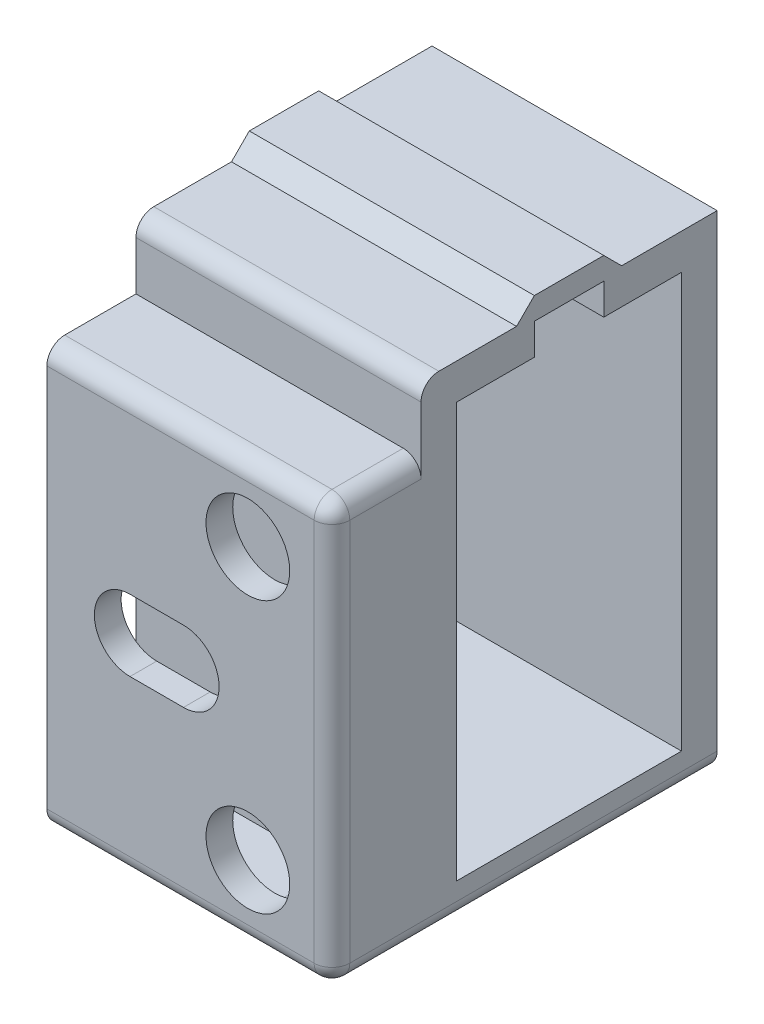
SolidWorks part; units mm, degrees
ref_plane "Front Plane" through (0, 0, 0) normal (0, 0, 1) x (1, 0, 0)
ref_plane "Top Plane" through (0, 0, 0) normal (0, 1, 0) x (1, 0, 0)
ref_plane "Right Plane" through (0, 0, 0) normal (1, 0, 0) x (0, 0, -1)
sketch "Sketch1" plane through (0, 0, 0) normal (1, 0, 0) x (0, 0, -1)
  line L16 (6.3079, 6.3079) -> (-6.3079, 6.3079)
  line L17 (-6.3079, 6.3079) -> (-6.3079, -16.9632)
  line L18 (-6.3079, -16.9632) -> (6.3079, -16.9632)
  line L22 (6.3079, -16.9632) -> (6.3079, 6.3079)
  line L23 (6.0579, 6.0579) -> (-6.0579, 6.0579)
  line L24 (6.0579, -16.7132) -> (6.0579, 6.0579)
  line L25 (-6.0579, -16.7132) -> (6.0579, -16.7132)
  line L26 (-6.0579, 6.0579) -> (-6.0579, -16.7132)
  line L27 (6.0579, 6.0579) -> (-6.0579, 6.0579) construction
  line L28 (6.0579, -16.7132) -> (6.0579, 6.0579) construction
  line L29 (-6.0579, -16.7132) -> (6.0579, -16.7132) construction
  line L30 (-6.0579, 6.0579) -> (-6.0579, -16.7132) construction
  line L31 (8.3079, 8.3079) -> (-8.3079, 8.3079)
  line L32 (-8.3079, 8.3079) -> (-8.3079, -18.9632)
  line L33 (-8.3079, -18.9632) -> (8.3079, -18.9632)
  line L34 (8.3079, -18.9632) -> (8.3079, 8.3079)
  dimension "D1" = 0
  dimension "D2" = 0.25
  dimension "D3" = 2
extrude "Boss-Extrude1" add sketch "Sketch1" along normal mid plane 16
sketch "Sketch2" plane through (-8, 0, 0) normal (-1, 0, 0) x (0, 0, 1)
  line L0 (-1.9478, 5.5579) -> (1.9478, 5.5579)
  line L1 (1.9478, 5.5579) -> (1.9478, 8.0579)
  line L3 (-1.9478, 8.0579) -> (-1.9478, 5.5579)
  line L4 (-1.4478, 6.0579) -> (1.4478, 6.0579)
  line L5 (1.4478, 6.0579) -> (1.4478, 12.1539)
  line L6 (1.4478, 12.1539) -> (-1.4478, 12.1539)
  line L7 (-1.4478, 12.1539) -> (-1.4478, 6.0579)
  line L8 (-1.4478, 6.0579) -> (1.4478, 6.0579) construction
  line L9 (1.4478, 6.0579) -> (1.4478, 12.1539) construction
  line L10 (1.4478, 12.1539) -> (-1.4478, 12.1539) construction
  line L11 (-1.4478, 12.1539) -> (-1.4478, 6.0579) construction
  line L12 (-1.9478, 8.0579) -> (1.9478, 8.0579)
  line L13 (-1.9478, 12.6539) -> (-1.9478, 5.5579) construction
  line L14 (1.9478, 12.6539) -> (-1.9478, 12.6539) construction
  line L15 (1.9478, 5.5579) -> (1.9478, 12.6539) construction
  dimension "D3" = 2
  dimension "D1" = 0
  dimension "D2" = 0.5
extrude "Cut-Extrude2" cut sketch "Sketch2" against normal through all
sketch "Sketch3" plane through (0, 0, 0) normal (0, 0, 1) x (1, 0, 0)
  line B0 (-15.4169, 7.595) -> (-15.4169, -7.595) construction
  line B1 (-12.7469, -10.265) -> (-0.3069, -10.265) construction
  line B2 (2.3631, -7.595) -> (2.3631, 7.595) construction
  line B3 (-0.3069, 10.265) -> (-12.7469, 10.265) construction
  circle B4 centre (-0.1369, -7.615) radius 1.2 construction
  circle B5 centre (-0.1369, 7.615) radius 1.2 construction
  arc B6 (-12.7469, 10.265) -> (-15.4169, 7.595) centre (-12.7469, 7.595) ccw construction
  arc B7 (-15.4169, -7.595) -> (-12.7469, -10.265) centre (-12.7469, -7.595) ccw construction
  arc B8 (-0.3069, -10.265) -> (2.3631, -7.595) centre (-0.3069, -7.595) ccw construction
  arc B9 (2.3631, 7.595) -> (-0.3069, 10.265) centre (-0.3069, 7.595) ccw construction
sketch_block_instance "Block1-1"
sketch_block "Block1"
sketch "Sketch5" plane through (0, 0, 8.3079) normal (0, 0, 1) x (1, 0, 0)
  line L0 (5.78, -7.1982) -> (0.4676, -7.1982) construction
  line L1 (-8, 8.3079) -> (-8, -18.9632) construction
  line L2 (8, 8.3079) -> (8, -18.9632) construction
  line L3 (8, -18.9632) -> (-8, -18.9632)
  line L4 (8, -18.9632) -> (8, 4.5668)
  line L5 (8, 4.5668) -> (-8, 4.5668)
  line L6 (-8, -18.9632) -> (-8, 4.5668)
  line L7 (3.11, 3.0668) -> (3.11, 4.5668) construction
  line L8 (3.11, -17.4632) -> (3.11, -18.9632) construction
  point P2 (-8, -22.0591)
  line B0 (-12, 0.3968) -> (-12, -14.7932) construction
  line B1 (-9.33, -17.4632) -> (3.11, -17.4632) construction
  line B2 (5.78, -14.7932) -> (5.78, 0.3968) construction
  line B3 (3.11, 3.0668) -> (-9.33, 3.0668) construction
  circle B4 centre (3.28, -14.8132) radius 1.2 construction
  circle B5 centre (3.28, 0.4168) radius 1.2 construction
  arc B6 (-9.33, 3.0668) -> (-12, 0.3968) centre (-9.33, 0.3968) ccw construction
  arc B7 (-12, -14.7932) -> (-9.33, -17.4632) centre (-9.33, -14.7932) ccw construction
  arc B8 (3.11, -17.4632) -> (5.78, -14.7932) centre (3.11, -14.7932) ccw construction
  arc B9 (5.78, 0.3968) -> (3.11, 3.0668) centre (3.11, 0.3968) ccw construction
  line M10 (-8, 8.3079) -> (-8, -18.9632)
  line M12 (8, -18.9632) -> (8, 8.3079)
  line M13 (8, 8.3079) -> (-8, 8.3079)
  dimension "D1" = 4
  dimension "D2" = 1.5
sketch_block_instance "Block1-4"
extrude "Boss-Extrude2" add sketch "Sketch5" along normal blind 0.0001 contours L3 M12 M13 M10 | L6 L4 L5 M13
hole_wizard "M2 Clearance Hole1" positions "Sketch6" profile "Sketch7" hole size "M2" standard "ANSI Metric"
sketch "Sketch6" plane through (0, 0, 8.308) normal (0, 0, 1) x (1, 0, 0)
  point P0 (3.28, 0.4168)
  point P2 (3.28, -14.8132)
sketch "Sketch7" plane through (3.28, 0.4168, 8.308) normal (1, 0, 0) x (0, -1, 0)
  line L0 (0, 0) -> (0, 2.7201)
  line L1 (0, 2.7201) -> (1.2, 1.9991)
  line L2 (1.2, 1.9991) -> (1.2, 0)
  line L5 (1.2, 0) -> (0, 0)
  line L10 (0, 2.7201) -> (-1.2, 1.9991) construction
  line L11 (0, -6.35) -> (0, 107.95) construction
  dimension "Hole Dia." = 2.4
  dimension "Hole Depth" = 1.9991
  dimension "Drill Angle" = 118
sketch "Sketch8" plane through (0, 0, 8.308) normal (0, 0, 1) x (1, 0, 0)
  line L4 (3.11, 3.0668) -> (-9.33, 3.0668) construction
  line L5 (5.78, -14.7932) -> (5.78, 0.3968) construction
  line L7 (-9.33, -17.4632) -> (3.11, -17.4632) construction
  line L14 (3.11, 3.0668) -> (-9.33, 3.0668) construction
  line L15 (5.78, -14.7932) -> (5.78, 0.3968) construction
  line L16 (-9.33, -17.4632) -> (3.11, -17.4632) construction
  line L28 (-8, -17.8132) -> (3.11, -17.8132)
  line L32 (6.13, -14.7932) -> (6.13, 0.3968)
  line L33 (3.11, 3.4168) -> (-8, 3.4168)
  line L34 (-8, 8.3079) -> (-8, -18.9632) construction
  line L35 (8, -18.9632) -> (-8, -18.9632)
  line L37 (8, -18.9632) -> (8, 4.5668)
  line L38 (8, 4.5668) -> (-8, 4.5668)
  line L39 (-8, -18.9632) -> (-8, -17.8132)
  line L40 (3.11, 3.4168) -> (-9.33, 3.4168) construction
  line L41 (-8, 3.4168) -> (-8, 4.5668)
  line L42 (-9.33, -17.8132) -> (3.11, -17.8132) construction
  arc A4 (5.78, 0.3968) -> (3.11, 3.0668) centre (3.11, 0.3968) ccw construction
  arc A5 (3.11, -17.4632) -> (5.78, -14.7932) centre (3.11, -14.7932) ccw construction
  arc A13 (5.78, 0.3968) -> (3.11, 3.0668) centre (3.11, 0.3968) ccw construction
  arc A14 (3.11, -17.4632) -> (5.78, -14.7932) centre (3.11, -14.7932) ccw construction
  arc A15 (3.11, -17.8132) -> (6.13, -14.7932) centre (3.11, -14.7932) ccw
  arc A16 (6.13, 0.3968) -> (3.11, 3.4168) centre (3.11, 0.3968) ccw
  dimension "D1" = 0.35
extrude "Boss-Extrude3" add sketch "Sketch8" along normal blind 3.5
sketch "Sketch9" plane through (0, 0, 11.808) normal (0, 0, 1) x (1, 0, 0)
  line L1 (8, 4.5668) -> (-8, 4.5668)
  line L2 (8, 4.5668) -> (8, -18.9632)
  line L3 (8, -18.9632) -> (-8, -18.9632)
  line L4 (-8, 4.5668) -> (-8, -18.9632)
  point P4 (8, 3.5668)
extrude "Boss-Extrude4" add sketch "Sketch9" along normal blind 1.5
sketch "Sketch10" plane through (0, 0, 13.308) normal (0, 0, 1) x (1, 0, 0)
  line L0 (-3.335, -7.1982) -> (-0.335, -7.1982) construction
  line L1 (-3.335, -5.1982) -> (-0.335, -5.1982)
  line L2 (-3.335, -9.1982) -> (-0.335, -9.1982)
  arc A0 (-3.335, -5.1982) -> (-3.335, -9.1982) centre (-3.335, -7.1982) ccw
  arc A1 (-0.335, -9.1982) -> (-0.335, -5.1982) centre (-0.335, -7.1982) ccw
  circle A2 centre (-3.335, -7.1982) radius 0.2 construction
  circle A3 centre (-3.335, -7.1982) radius 0.2 construction
  circle A4 centre (-0.335, -7.1982) radius 0.1 construction
  circle A5 centre (-0.335, -7.1982) radius 0.1 construction
  circle A6 centre (3.28, 0.4168) radius 2.35
  circle A7 centre (3.28, -14.8132) radius 2.35
  circle A8 centre (3.28, -14.8132) radius 1.2 construction
  circle A9 centre (3.28, -14.8132) radius 1.2 construction
  circle A10 centre (3.28, 0.4168) radius 1.2 construction
  circle A11 centre (3.28, 0.4168) radius 1.2 construction
  point P3 (-1.835, -7.1982)
  dimension "D2" = 4.7
  dimension "D1" = 4
extrude "Cut-Extrude3" cut sketch "Sketch10" against normal up to surface (1.5 mm away) up to face at (0.6218, -7.1982, 11.808)
fillet "Fillet1" radius 1 6 edges at (8, -18.9632, 2.5) (0, -18.9632, 13.308) (8, -7.1982, 13.308) (8, 4.5668, 10.808) (0, 4.5668, 13.308) (0, 8.3079, 8.308)
sketch "Sketch11" plane through (-8, 0, 0) normal (-1, 0, 0) x (0, 0, 1)
  line L0 (2.9478, 8.3079) -> (1.9478, 9.3079)
  line L1 (-8.3079, 8.3079) -> (7.308, 8.3079) construction
  line L2 (1.9478, 9.3079) -> (-1.9478, 9.3079)
  line L3 (-1.9478, 9.3079) -> (-2.9478, 8.3079)
  line L4 (-2.9478, 8.3079) -> (2.9478, 8.3079)
  line L5 (1.9478, 6.3079) -> (1.9478, 8.0579) construction
  line L6 (-1.9478, 8.0579) -> (-1.9478, 6.3079) construction
  line L7 (0, 8.3079) -> (0, 9.3079) construction
  dimension "D1" = 45
  dimension "D2" = 1
extrude "Boss-Extrude5" add sketch "Sketch11" against normal up to surface (16 mm away) up to face at (8, 0.9276, 0)
